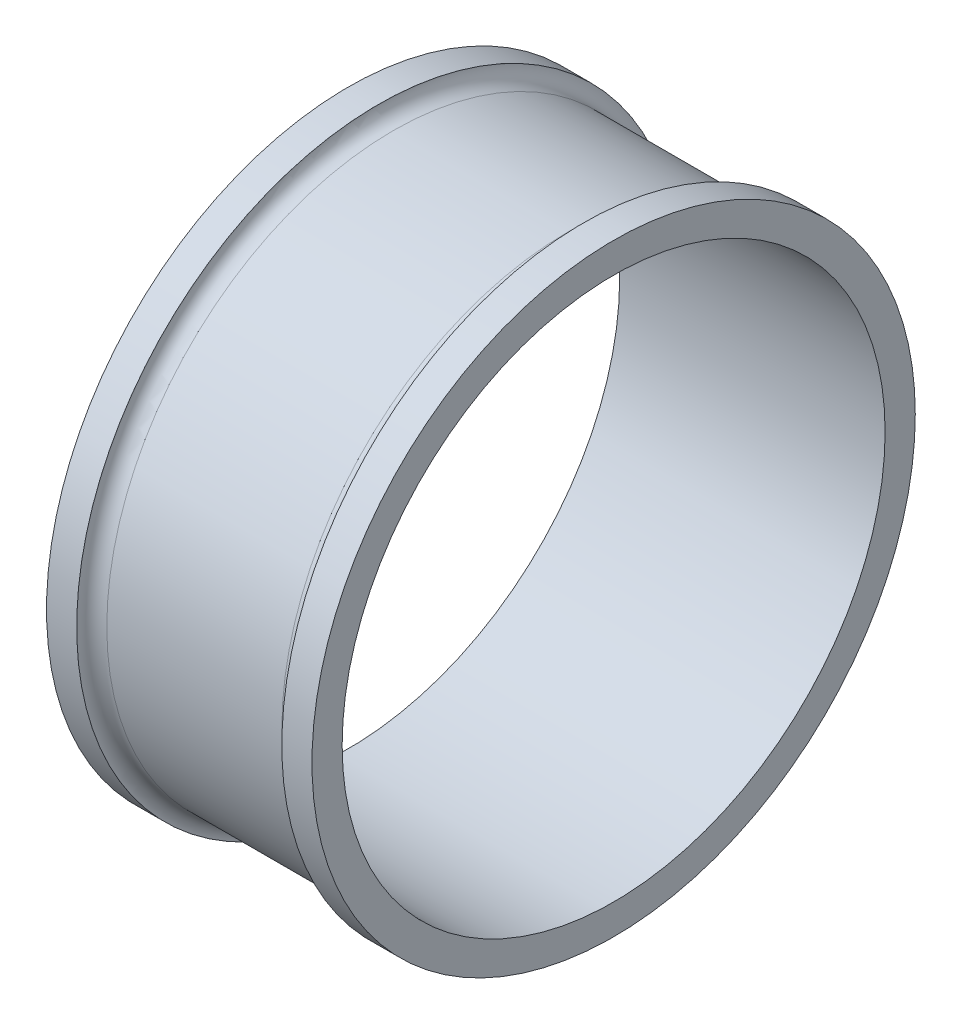
SolidWorks part; units mm, degrees
ref_plane "Front Plane" through (0, 0, 0) normal (0, 0, 1) x (1, 0, 0)
ref_plane "Top Plane" through (0, 0, 0) normal (0, 1, 0) x (1, 0, 0)
ref_plane "Right Plane" through (0, 0, 0) normal (1, 0, 0) x (0, 0, -1)
sketch "Sketch1" plane through (0, 0, 0) normal (0, 0, 1) x (1, 0, 0)
  line L0 (0, -43.0319) -> (0, 39.8404) construction
  line L1 (62.9787, 0) -> (-83.0851, 0) construction
  line L2 (22, 45) -> (-22, 45)
  line L3 (-22, 45) -> (-22, 50)
  line L4 (-22, 50) -> (-17, 50)
  line L5 (-17, 50) -> (-17, 49.99)
  line L6 (-14.51, 47.5) -> (14.51, 47.5)
  line L7 (22, 45) -> (22, 50)
  line L8 (22, 50) -> (17, 50)
  line L9 (17, 50) -> (17, 49.99)
  arc A0 (-17, 49.99) -> (-14.51, 47.5) centre (-14.51, 49.99) ccw
  arc A1 (17, 49.99) -> (14.51, 47.5) centre (14.51, 49.99) cw
  point P7 (-22, 47.5)
  point P14 (-17, 47.5)
  point P16 (0, 45)
  point P21 (0, 47.5)
  dimension "D5" = 2.49
  dimension "D1" = 5
  dimension "D2" = 5
  dimension "D3" = 2.5
  dimension "D4" = 44
  dimension "D6" = 95
revolve "Revolve1" add sketch "Sketch1" angle 360 about L1
